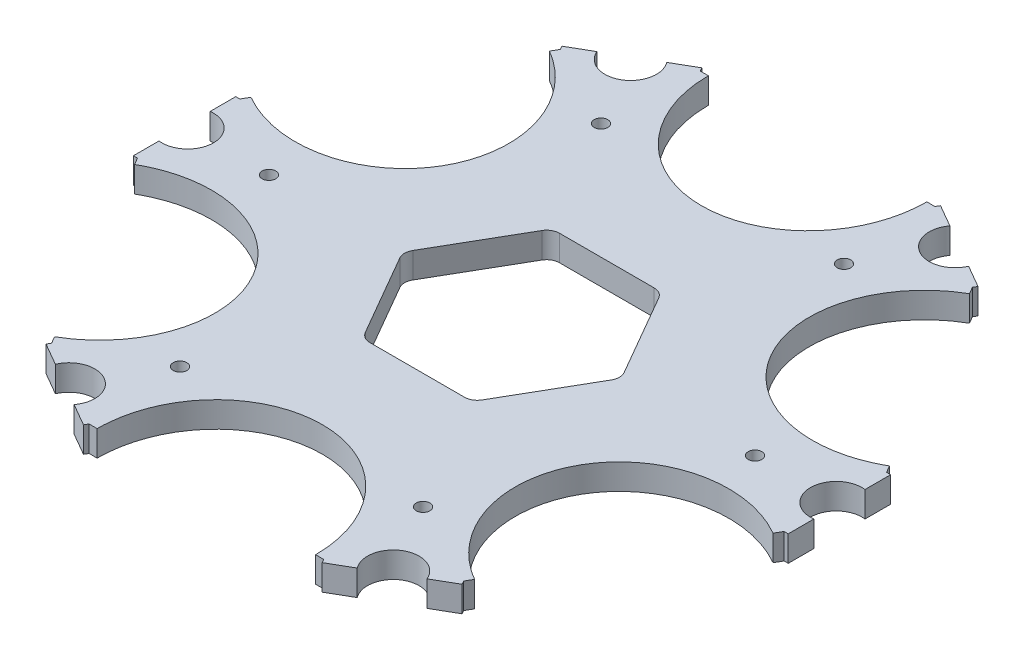
SolidWorks part; units mm, degrees
material "6061-T6 (SS)"
ref_plane "X-Y Datum" through (0, 0, 0) normal (0, 0, 1) x (1, 0, 0)
ref_plane "X-Z Datum" through (0, 0, 0) normal (0, 1, 0) x (1, 0, 0)
ref_plane "Y-Z Datum" through (0, 0, 0) normal (1, 0, 0) x (0, 0, -1)
sketch "Sketch1" plane through (0, 0, 0) normal (0, 1, 0) x (1, 0, 0)
  line L0 (-60.325, 0) -> (-60.325, -50000) construction
  line L1 (-60.1472, 5.5534) -> (-60.1472, 9.525)
  line L2 (-2.3269, 0) -> (49997.6731, 0) construction
  line L3 (0, 0) -> (-35355.3391, 35355.3391) construction
  line L4 (-60.1472, -5.5534) -> (-60.1472, -9.525)
  line L5 (-25.2642, 54.8657) -> (-21.8247, 56.8515)
  line L6 (-34.883, 49.3123) -> (-38.3225, 47.3265)
  line L7 (34.883, 49.3123) -> (38.3225, 47.3265)
  line L8 (25.2642, 54.8657) -> (21.8247, 56.8515)
  line L9 (60.1472, -5.5534) -> (60.1472, -9.525)
  line L10 (60.1472, 5.5534) -> (60.1472, 9.525)
  line L11 (25.2642, -54.8657) -> (21.8247, -56.8515)
  line L12 (34.883, -49.3123) -> (38.3225, -47.3265)
  line L13 (-34.883, -49.3123) -> (-38.3225, -47.3265)
  line L14 (-25.2642, -54.8657) -> (-21.8247, -56.8515)
  line L15 (-60.1472, 9.525) -> (-38.3225, 47.3265)
  line L16 (-21.8247, 56.8515) -> (21.8247, 56.8515)
  line L17 (38.3225, 47.3265) -> (60.1472, 9.525)
  line L18 (60.1472, -9.525) -> (38.3225, -47.3265)
  line L19 (21.8247, -56.8515) -> (-21.8247, -56.8515)
  line L20 (-38.3225, -47.3265) -> (-60.1472, -9.525)
  circle A0 centre (0, 0) radius 60.325 construction
  circle A1 centre (0, 0) radius 69.85 construction
  arc A2 (-60.1472, -5.5534) -> (-60.1472, 5.5534) centre (-60.325, 0) ccw
  arc A3 (-34.883, 49.3123) -> (-25.2642, 54.8657) centre (-30.1625, 52.243) ccw
  arc A4 (25.2642, 54.8657) -> (34.883, 49.3123) centre (30.1625, 52.243) ccw
  arc A5 (60.1472, 5.5534) -> (60.1472, -5.5534) centre (60.325, 0) ccw
  arc A6 (34.883, -49.3123) -> (25.2642, -54.8657) centre (30.1625, -52.243) ccw
  arc A7 (-25.2642, -54.8657) -> (-34.883, -49.3123) centre (-30.1625, -52.243) ccw
  circle A8 centre (0, 0) radius 12.7
  point P31 (0, 0)
  point P41 (0, 0)
  point P42 (0, 0)
  point P43 (0, 0)
  point P44 (0, 0)
  point P45 (0, 0)
  dimension "D1" = 120.65
  dimension "D2" = 139.7
  dimension "D7" = 25.4
  dimension "D8" = 5.5563
  dimension "D3" = 19.05
  dimension "D4" = 0.1778
  dimension "D5" = 45
extrude "Boss-Extrude1" add sketch "Sketch1" along normal mid plane 4.7625
sketch "Sketch2" plane through (0, 2.3813, 0) normal (0, 1, 0) x (1, 0, 0)
  line L1 (10.6172, -18.3896) -> (21.2345, 0)
  line L2 (21.2345, 0) -> (10.6172, 18.3896)
  line L3 (10.6172, 18.3896) -> (-10.6172, 18.3896)
  line L4 (-10.6172, 18.3896) -> (-21.2345, 0)
  line L5 (-21.2345, 0) -> (-10.6172, -18.3896)
  line L6 (-10.6172, -18.3896) -> (10.6172, -18.3896)
  circle A0 centre (0, 0) radius 18.3896 construction
  dimension "D1" = 36.7792
extrude "Cut-Extrude1" cut sketch "Sketch2" against normal through all
ref_axis "Wheel Axis" through (0, -55, 0) along (0, 1, 0)
fillet "Fillet1" radius 3.175 6 edges at (-21.2345, 0, 0) (-10.6172, 0, -18.3896) (21.2345, 0, 0) (10.6172, 0, -18.3896) (-10.6172, 0, 18.3896) (10.6172, 0, 18.3896)
sketch "Sketch3" plane through (0, 2.3813, 0) normal (0, 1, 0) x (1, 0, 0)
  line L7 (-21.8247, -56.8515) -> (21.8247, -56.8515) construction
  ellipse E0 centre (0, -56.8515) end of major axis (0, -78.4415) minor radius 20.32
  dimension "D1" = 40.64
  dimension "D2" = 21.59
extrude "Cut-Extrude2" cut sketch "Sketch3" against normal through all
pattern_circular "CirPattern1" count 6 over 360 about axis through (0, -55, 0) along (0, 1, 0) of "Cut-Extrude2"
sketch "Sketch4" plane through (0, 2.3813, 0) normal (0, 1, 0) x (1, 0, 0)
  circle A0 centre (45.212, 0) radius 1.27
extrude "Cut-Extrude3" cut sketch "Sketch4" against normal through all
sketch "Sketch5" plane through (0, 0, 0) normal (0, 0, 1) x (1, 0, 0)
  line L0 (0, 0) -> (0, 9.4144) construction
pattern_circular "CirPattern2" count 6 over 360 about axis through (0, 0, 0) along (0, 1, 0) of "Cut-Extrude3"
sketch "Sketch6" plane through (0, 2.3813, 0) normal (0, 1, 0) x (1, 0, 0)
  line L0 (11.5338, -16.8021) -> (20.3179, -1.5875) construction
  line L1 (-8.7842, -18.3896) -> (8.7842, -18.3896) construction
  line L2 (-20.3179, -1.5875) -> (-11.5338, -16.8021) construction
  line L3 (20.3179, 1.5875) -> (11.5338, 16.8021) construction
  line L4 (8.7842, 18.3896) -> (-8.7842, 18.3896) construction
  line L5 (-11.5338, 16.8021) -> (-20.3179, 1.5875) construction
  line L6 (11.5338, -16.8021) -> (20.3179, -1.5875)
  line L7 (-8.7842, -18.3896) -> (8.7842, -18.3896)
  line L8 (-20.3179, -1.5875) -> (-11.5338, -16.8021)
  line L9 (20.3179, 1.5875) -> (11.5338, 16.8021)
  line L10 (8.7842, 18.3896) -> (-8.7842, 18.3896)
  line L11 (-11.5338, 16.8021) -> (-20.3179, 1.5875)
  line L12 (-60.1472, -5.5534) -> (-60.1472, -9.525) construction
  line L13 (-60.1472, 9.525) -> (-60.1472, 5.5534) construction
  line L14 (-60.1472, -5.5534) -> (-60.1472, -9.525)
  line L15 (-60.1472, 9.525) -> (-60.1472, 5.5534)
  line L16 (-34.883, 49.3123) -> (-38.3225, 47.3265)
  line L17 (-21.8247, 56.8515) -> (-25.2642, 54.8657)
  line L18 (-22.2057, 57.5114) -> (-21.8247, 56.8515)
  line L19 (-22.2057, 57.5114) -> (-26.3336, 55.1282)
  line L20 (-34.5756, 50.3697) -> (-38.7035, 47.9864)
  line L21 (-38.7035, 47.9864) -> (-38.3225, 47.3265)
  line L22 (25.2642, 54.8657) -> (21.8247, 56.8515)
  line L23 (38.3225, 47.3265) -> (34.883, 49.3123)
  line L24 (38.7035, 47.9864) -> (38.3225, 47.3265)
  line L25 (38.7035, 47.9864) -> (34.5756, 50.3697)
  line L26 (26.3336, 55.1282) -> (22.2057, 57.5114)
  line L27 (22.2057, 57.5114) -> (21.8247, 56.8515)
  line L28 (60.1472, 5.5534) -> (60.1472, 9.525)
  line L29 (60.1472, -9.525) -> (60.1472, -5.5534)
  line L30 (60.9092, -9.525) -> (60.1472, -9.525)
  line L31 (60.9092, -9.525) -> (60.9092, -4.7585)
  line L32 (60.9092, 4.7585) -> (60.9092, 9.525)
  line L33 (60.9092, 9.525) -> (60.1472, 9.525)
  line L34 (34.883, -49.3123) -> (38.3225, -47.3265)
  line L35 (21.8247, -56.8515) -> (25.2642, -54.8657)
  line L36 (22.2057, -57.5114) -> (21.8247, -56.8515)
  line L37 (22.2057, -57.5114) -> (26.3336, -55.1282)
  line L38 (34.5756, -50.3697) -> (38.7035, -47.9864)
  line L39 (38.7035, -47.9864) -> (38.3225, -47.3265)
  line L40 (-25.2642, -54.8657) -> (-21.8247, -56.8515)
  line L41 (-38.3225, -47.3265) -> (-34.883, -49.3123)
  line L42 (-38.7035, -47.9864) -> (-38.3225, -47.3265)
  line L43 (-38.7035, -47.9864) -> (-34.5756, -50.3697)
  line L44 (-26.3336, -55.1282) -> (-22.2057, -57.5114)
  line L45 (-22.2057, -57.5114) -> (-21.8247, -56.8515)
  line L47 (-60.9092, 9.525) -> (-60.1472, 9.525)
  line L49 (19.658, 1.2065) -> (10.8739, 16.4211)
  line L50 (10.8739, -16.4211) -> (19.658, -1.2065)
  line L51 (-8.7842, -17.6276) -> (8.7842, -17.6276)
  line L52 (-19.658, -1.2065) -> (-10.8739, -16.4211)
  line L53 (-10.8739, 16.4211) -> (-19.658, 1.2065)
  line L54 (8.7842, 17.6276) -> (-8.7842, 17.6276)
  line L55 (19.658, 1.2065) -> (10.8739, 16.4211)
  line L56 (10.8739, -16.4211) -> (19.658, -1.2065)
  line L57 (-8.7842, -17.6276) -> (8.7842, -17.6276)
  line L58 (-19.658, -1.2065) -> (-10.8739, -16.4211)
  line L59 (-10.8739, 16.4211) -> (-19.658, 1.2065)
  line L60 (8.7842, 17.6276) -> (-8.7842, 17.6276)
  line L61 (-60.9092, 9.525) -> (-60.9092, 4.7585)
  line L62 (-60.9092, -4.7585) -> (-60.9092, -9.525)
  line L63 (-60.9092, 9.525) -> (-60.9092, 4.7585)
  line L64 (-60.9092, -4.7585) -> (-60.9092, -9.525)
  line L66 (-60.9092, -9.525) -> (-60.1472, -9.525)
  arc A0 (20.3179, -1.5875) -> (20.3179, 1.5875) centre (17.5683, 0) ccw construction
  arc A1 (8.7842, -18.3896) -> (11.5338, -16.8021) centre (8.7842, -15.2146) ccw construction
  arc A2 (-11.5338, -16.8021) -> (-8.7842, -18.3896) centre (-8.7842, -15.2146) ccw construction
  arc A3 (-20.3179, 1.5875) -> (-20.3179, -1.5875) centre (-17.5683, 0) ccw construction
  arc A4 (11.5338, 16.8021) -> (8.7842, 18.3896) centre (8.7842, 15.2146) ccw construction
  arc A5 (-8.7842, 18.3896) -> (-11.5338, 16.8021) centre (-8.7842, 15.2146) ccw construction
  arc A6 (20.3179, -1.5875) -> (20.3179, 1.5875) centre (17.5683, 0) ccw
  arc A7 (8.7842, -18.3896) -> (11.5338, -16.8021) centre (8.7842, -15.2146) ccw
  arc A8 (-11.5338, -16.8021) -> (-8.7842, -18.3896) centre (-8.7842, -15.2146) ccw
  arc A9 (-20.3179, 1.5875) -> (-20.3179, -1.5875) centre (-17.5683, 0) ccw
  arc A10 (11.5338, 16.8021) -> (8.7842, 18.3896) centre (8.7842, 15.2146) ccw
  arc A11 (-8.7842, 18.3896) -> (-11.5338, 16.8021) centre (-8.7842, 15.2146) ccw
  arc A12 (-60.1472, -5.5534) -> (-60.1472, 5.5534) centre (-60.325, 0) ccw construction
  arc A13 (-60.1472, -5.5534) -> (-60.1472, 5.5534) centre (-60.325, 0) ccw
  arc A14 (-34.883, 49.3123) -> (-25.2642, 54.8657) centre (-30.1625, 52.243) ccw
  arc A15 (-34.5756, 50.3697) -> (-26.3336, 55.1282) centre (-30.1625, 52.243) ccw
  arc A16 (25.2642, 54.8657) -> (34.883, 49.3123) centre (30.1625, 52.243) ccw
  arc A17 (26.3336, 55.1282) -> (34.5756, 50.3697) centre (30.1625, 52.243) ccw
  arc A18 (60.1472, 5.5534) -> (60.1472, -5.5534) centre (60.325, 0) ccw
  arc A19 (60.9092, 4.7585) -> (60.9092, -4.7585) centre (60.325, 0) ccw
  arc A20 (34.883, -49.3123) -> (25.2642, -54.8657) centre (30.1625, -52.243) ccw
  arc A21 (34.5756, -50.3697) -> (26.3336, -55.1282) centre (30.1625, -52.243) ccw
  arc A22 (-25.2642, -54.8657) -> (-34.883, -49.3123) centre (-30.1625, -52.243) ccw
  arc A23 (-26.3336, -55.1282) -> (-34.5756, -50.3697) centre (-30.1625, -52.243) ccw
  arc A38 (-60.9092, -4.7585) -> (-60.9092, 4.7585) centre (-60.325, 0) ccw
  arc A39 (-60.9092, -4.7585) -> (-60.9092, 4.7585) centre (-60.325, 0) ccw
  arc A41 (10.8739, 16.4211) -> (8.7842, 17.6276) centre (8.7842, 15.2146) ccw
  arc A42 (19.658, -1.2065) -> (19.658, 1.2065) centre (17.5683, 0) ccw
  arc A43 (8.7842, -17.6276) -> (10.8739, -16.4211) centre (8.7842, -15.2146) ccw
  arc A44 (-10.8739, -16.4211) -> (-8.7842, -17.6276) centre (-8.7842, -15.2146) ccw
  arc A45 (-19.658, 1.2065) -> (-19.658, -1.2065) centre (-17.5683, 0) ccw
  arc A46 (-8.7842, 17.6276) -> (-10.8739, 16.4211) centre (-8.7842, 15.2146) ccw
  arc A47 (10.8739, 16.4211) -> (8.7842, 17.6276) centre (8.7842, 15.2146) ccw
  arc A48 (19.658, -1.2065) -> (19.658, 1.2065) centre (17.5683, 0) ccw
  arc A49 (8.7842, -17.6276) -> (10.8739, -16.4211) centre (8.7842, -15.2146) ccw
  arc A50 (-10.8739, -16.4211) -> (-8.7842, -17.6276) centre (-8.7842, -15.2146) ccw
  arc A51 (-19.658, 1.2065) -> (-19.658, -1.2065) centre (-17.5683, 0) ccw
  arc A52 (-8.7842, 17.6276) -> (-10.8739, 16.4211) centre (-8.7842, 15.2146) ccw
  point P80 (0, 0)
  dimension "D1" = 0.762
  dimension "D2" = 0.762
  dimension "D3" = 6
extrude "Boss-Extrude2" add sketch "Sketch6" against normal up to surface (4.7625 mm away) up to face at (23.7059, -2.3813, -38.5197)
